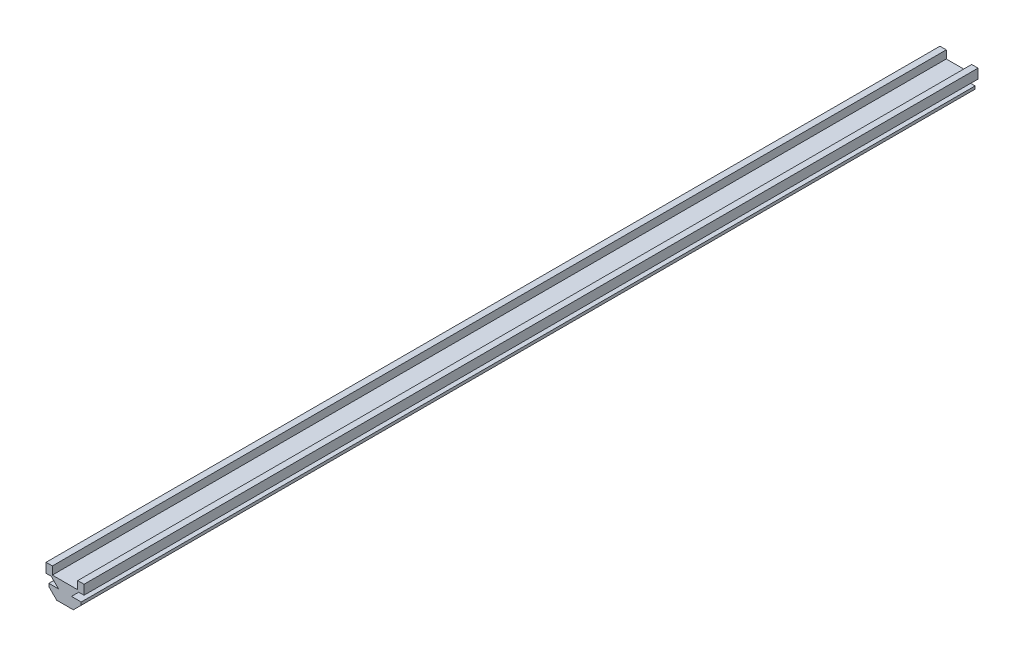
SolidWorks part; units mm, degrees
ref_plane "Alzado" through (0, 0, 0) normal (0, 0, 1) x (1, 0, 0)
ref_plane "Planta" through (0, 0, 0) normal (0, 1, 0) x (1, 0, 0)
ref_plane "Vista lateral" through (0, 0, 0) normal (1, 0, 0) x (0, 0, -1)
sketch "Croquis1" plane through (0, 0, 0) normal (0, 0, 1) x (1, 0, 0)
  line L0 (12.6279, -5.675) -> (15.1, -3.2029)
  line L8 (7.1649, -6.175) -> (10, -6.175)
  line L9 (15.1, -2.3) -> (15.1, -3.2029)
  line L10 (15.1, -2.3) -> (12.0429, -2.3)
  line L12 (7.3721, -5.675) -> (12.6279, -5.675)
  line L13 (10, -6.175) -> (10, 0.5) construction
  line L33 (7.3721, -5.675) -> (4.9, -3.2029)
  line L34 (4.9, -2.3) -> (4.9, -3.2029)
  line L35 (4.9, -2.3) -> (7.9571, -2.3)
  line L41 (12.0429, -2.3) -> (14.3429, 0)
  line L42 (7.9571, -2.3) -> (5.6571, 0)
  line L43 (14.3429, 0) -> (16, 0)
  line L49 (16, 0) -> (16, 3)
  line L50 (14, 3) -> (16, 3)
  line L51 (10, 0.5) -> (10, -6.175)
  line L54 (6, 0.5) -> (14, 0.5)
  line L56 (14, 0.5) -> (14, 3)
  line L62 (5.6571, 0) -> (4, 0)
  line L65 (7.1649, -6.175) -> (4.4, -3.4101)
  line L66 (4.4, -1.8) -> (4.4, -3.4101)
  line L67 (4.4, -1.8) -> (6.75, -1.8)
  line L68 (6.75, -1.8) -> (4.95, 0)
  line L69 (0, 0) -> (4.4, 0)
  line L70 (4.4, 0) -> (4.95, 0)
  line L75 (6, 0.5) -> (6, 3)
  line L76 (6, 3) -> (4, 3)
  line L77 (4, 0) -> (4, 3)
  line L89 (10, 0.5) -> (6, 0.5)
  point P3 (10, -5.675)
  dimension "D1" = 10
  dimension "D2" = 4
  dimension "D5" = 2
  dimension "D4" = 3
  dimension "D6" = 0.5
extrude "Saliente-Extruir1" add sketch "Croquis1" along normal blind 282 contours L77 L62 L42 L35 L34 L33 L12 L51 L54 L75 L76 | L56 L54 L51 L12 L0 L9 L10 L41 L43 L49 L50
